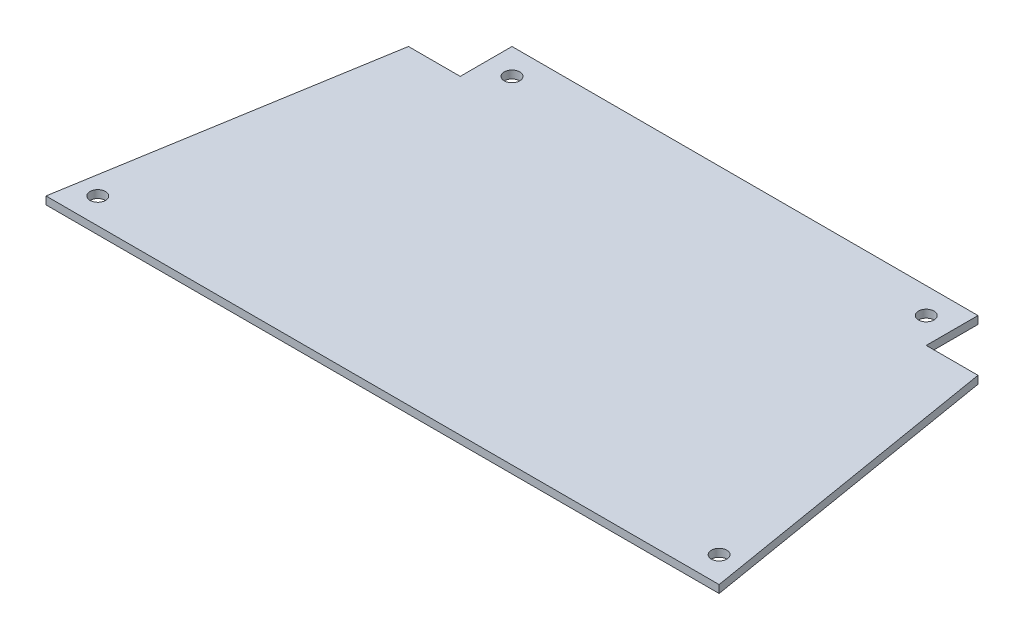
SolidWorks part; units mm, degrees
ref_plane "Ön Düzlem" through (0, 0, 0) normal (0, 0, 1) x (1, 0, 0)
ref_plane "Üst Düzlem" through (0, 0, 0) normal (0, 1, 0) x (1, 0, 0)
ref_plane "Sağ Düzlem" through (0, 0, 0) normal (1, 0, 0) x (0, 0, -1)
sketch "Çizim1" plane through (0, 0, 0) normal (0, 1, 0) x (1, 0, 0)
  line L0 (0, 0) -> (130, 0)
  line L1 (130, 0) -> (120, 60)
  line L2 (120, 60) -> (110, 60)
  line L3 (110, 60) -> (110, 70)
  line L4 (110, 70) -> (20, 70)
  line L5 (20, 70) -> (20, 60)
  line L6 (20, 60) -> (10, 60)
  line L7 (10, 60) -> (0, 0)
  line L8 (65, 0) -> (65, 70) construction
  dimension "D1" = 130
  dimension "D2" = 70
  dimension "D3" = 10
  dimension "D4" = 10
  dimension "D5" = 90
extrude "Yükseklik-Ekstrüzyon1" add sketch "Çizim1" along normal blind 1.5
sketch "Çizim2" plane through (0, 1.5, 0) normal (0, 1, 0) x (1, 0, 0)
  line L0 (110, 70) -> (20, 70) construction
  line L1 (20, 70) -> (20, 60) construction
  line L2 (0, 0) -> (130, 0) construction
  line L3 (65, 0) -> (65, 49.0509) construction
  line L4 (110, 60) -> (110, 70) construction
  circle A0 centre (25, 65) radius 1.5
  circle A1 centre (105, 65) radius 1.5
  circle A2 centre (5, 5) radius 1.5
  circle A3 centre (125, 5) radius 1.5
  dimension "D1" = 3
  dimension "D2" = 5
  dimension "D4" = 3
  dimension "D5" = 5
  dimension "D6" = 5
  dimension "D7" = 3
  dimension "D8" = 5
  dimension "D9" = 5
  dimension "D10" = 3
  dimension "D12" = 5
  dimension "D3" = 5
  dimension "D11" = 5
extrude "Kes-Ekstrüzyon1" cut sketch "Çizim2" against normal blind 10
